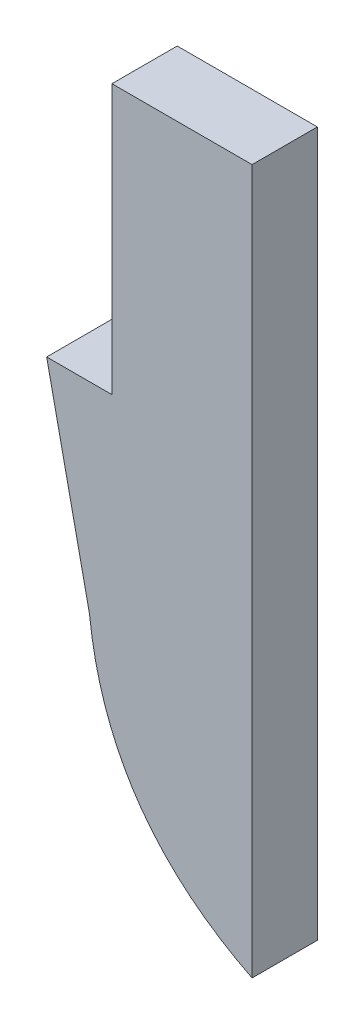
SolidWorks part; units mm, degrees
ref_plane "Спереди" through (0, 0, 0) normal (0, 0, 1) x (1, 0, 0)
ref_plane "Сверху" through (0, 0, 0) normal (0, 1, 0) x (1, 0, 0)
ref_plane "Справа" through (0, 0, 0) normal (1, 0, 0) x (0, 0, -1)
sketch "Эскиз1" plane through (0, 0, 0) normal (0, 0, 1) x (1, 0, 0)
  line L0 (-82.4248, -3.6979) -> (-73.8381, -3.6979)
  line L2 (-73.8381, -3.6979) -> (-73.8381, -46.8597)
  line L3 (-82.4248, -3.6979) -> (-82.4248, -20.1979)
  line L4 (-82.4248, -20.1979) -> (-86.4248, -20.1979)
  line L5 (-86.4248, -20.1979) -> (-83.7954, -32.5548)
  spline S0 degree 2 poles (-83.7954, -32.5548) (-82.721, -42.4102) (-73.8381, -46.8597) knots 0 0 0 1 1 1
extrude "Бобышка-Вытянуть1" add sketch "Эскиз1" along normal blind 4
